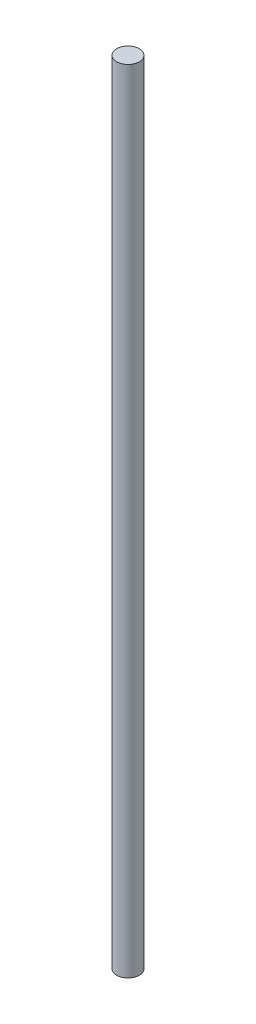
SolidWorks part; units mm, degrees
ref_plane "Plan de face" through (0, 0, 0) normal (0, 0, 1) x (1, 0, 0)
ref_plane "Plan de dessus" through (0, 0, 0) normal (0, 1, 0) x (1, 0, 0)
ref_plane "Plan de droite" through (0, 0, 0) normal (1, 0, 0) x (0, 0, -1)
sketch "Sketch1" plane through (0, 0, 0) normal (0, 1, 0) x (1, 0, 0)
  circle A0 centre (0, 0) radius 4
  dimension "D1" = 8
extrude "Boss-Extrude1" add sketch "Sketch1" along normal blind 280
